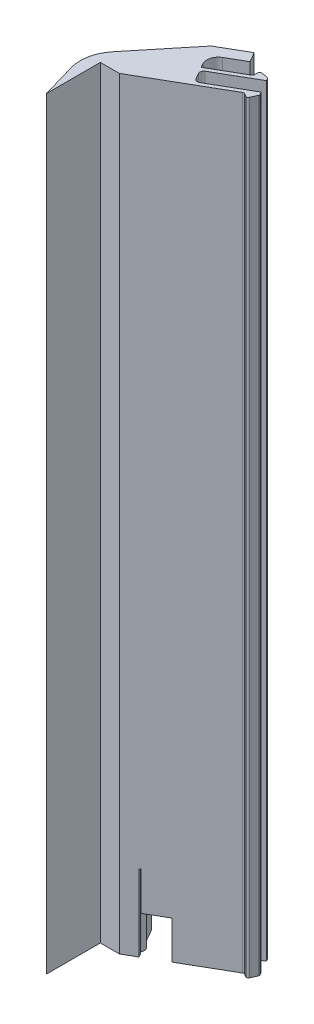
SolidWorks part; units mm, degrees
ref_plane "Front Plane" through (0, 0, 0) normal (0, 0, 1) x (1, 0, 0)
ref_plane "Top Plane" through (0, 0, 0) normal (0, 1, 0) x (1, 0, 0)
ref_plane "Right Plane" through (0, 0, 0) normal (1, 0, 0) x (0, 0, -1)
sketch "Sketch1" plane through (0, 0, 0) normal (0, 1, 0) x (1, 0, 0)
  line L0 (13.9271, 14.1754) -> (16.352, 13.8433)
  line L1 (16.352, 13.8433) -> (16.852, 12.9773)
  line L2 (13.9271, 14.1754) -> (13.9271, 12.4433)
  line L3 (2.5947, 5.9005) -> (3.0596, 5.0142)
  line L4 (13.9271, 12.4433) -> (2.5947, 5.9005)
  line L5 (18.752, 9.6864) -> (19.252, 8.8204)
  line L6 (19.252, 8.8204) -> (18.1539, 6.4543)
  line L7 (18.1539, 6.4543) -> (16.6539, 7.3204)
  line L8 (16.6539, 7.3204) -> (5.1142, 0.6579)
  line L9 (16.852, 12.9773) -> (3.0596, 5.0142)
  line L10 (18.752, 9.6864) -> (4.7191, 1.5845)
  line L11 (4.7191, 1.5845) -> (5.1142, 0.6579)
  dimension "D1" = 1
  dimension "D2" = 1
  dimension "D3" = 2.5
  dimension "D4" = 1
  dimension "D5" = 1
  dimension "D6" = 60
  dimension "D7" = 60
  dimension "D8" = 3
  dimension "D9" = 2.5
  dimension "D10" = 3.8
extrude "Boss-Extrude1" add sketch "Sketch1" along normal blind 200
fillet "Fillet1" radius 0.5 3 edges at (19.252, 100, -8.8204) (18.1539, 100, -6.4543) (16.6539, 100, -7.3204)
fillet "Fillet2" radius 0.5 3 edges at (16.352, 100, -13.8433) (13.9271, 100, -14.1754) (13.9271, 100, -12.4433)
sketch "Sketch2" plane through (0, 0, 0) normal (0, 1, 0) x (1, 0, 0)
  line L0 (8.1826, 2.4295) -> (3.2326, 11.0031)
  line L1 (5.1142, 0.6579) -> (16.4039, 7.176) construction
  line L2 (1.7326, 13.6012) -> (-13.1637, -4.6475)
  line L3 (-13.1637, -4.6475) -> (-9.0751, -18.7873)
  line L4 (-9.0751, -5.3031) -> (-9.0751, -305.3031) construction
  line L5 (-9.0751, -18.7873) -> (-9.0751, -4.6475)
  line L6 (-9.0751, -4.6475) -> (-4.0751, -4.6475)
  line L7 (8.1826, 2.4295) -> (-4.0751, -4.6475)
  line L8 (9.6431, 16.4363) -> (12.0181, 12.3227) construction
  line L9 (14.3058, 20.8603) -> (10.1922, 18.4853) construction
  line L10 (-4.0751, -5.3031) -> (-9.0751, -5.3031) construction
  line L11 (-4.0751, 60.1969) -> (-4.0751, -370.8031) construction
  line L12 (3.2326, 11.0031) -> (10.3931, 15.1372)
  line L13 (10.3931, 15.1372) -> (8.8931, 17.7353)
  line L14 (8.8931, 17.7353) -> (1.7326, 13.6012)
  dimension "D1" = 3
extrude "Boss-Extrude3" add sketch "Sketch2" along normal up to surface (200 mm away) up to face at (12.3433, 200, -11.5854)
fillet "Fillet3" radius 10 1 edges at (-13.1637, 100, 4.6475)
fillet "Fillet4" radius 1 2 edges at (5.7826, 100, -6.5864) (7.6826, 100, -3.2955)
fillet "Fillet5" radius 3 1 edges at (3.2326, 100, -11.0031)
sketch "Sketch3" plane through (0, 0, 0) normal (0, 1, 0) x (1, 0, 0)
  line L0 (-6.5899, 8.0163) -> (-2.3136, 0.6095)
  line L1 (-1.5636, -0.6895) -> (0.9704, -5.0785)
  line L2 (5.2826, 7.4524) -> (4.7326, 8.4051) construction
  line L7 (7.1826, 4.1615) -> (6.2826, 5.7204) construction
  line L8 (6.7326, 4.941) -> (-4.7829, -1.7076) construction
  line L9 (-4.0751, -4.6475) -> (16.4039, 7.176) construction
  line L10 (-6.9363, 7.8163) -> (-3.1217, 1.2092)
  line L11 (-1.4483, -1.6892) -> (0.6239, -5.2785)
  line L12 (-6.9363, 7.8163) -> (-6.5899, 8.0163)
  line L13 (0.6239, -5.2785) -> (0.9704, -5.0785)
  arc A0 (-2.3136, 0.6095) -> (-1.5636, -0.6895) centre (-3.0627, -0.689) ccw
  arc A2 (-3.1217, 1.2092) -> (-1.4483, -1.6892) centre (-3.0627, -0.689) ccw
  dimension "D1" = 1.5
  dimension "D2" = 10
  dimension "D3" = 0.4
extrude "Cut-Extrude2" cut sketch "Sketch3" along normal blind 20
sketch "Sketch4" plane through (0, 0, 0) normal (0, 1, 0) x (1, 0, 0)
  line L0 (-2.3136, 0.6095) -> (-5.0307, 5.3158)
  line L2 (-5.0307, 5.3158) -> (-2.0554, 8.9607)
  line L3 (1.7326, 13.6012) -> (-5.0307, 5.3158) construction
  line L4 (-2.0554, 8.9607) -> (4.6933, 0.4149)
  line L5 (-0.4776, -2.5705) -> (16.4039, 7.176) construction
  line L6 (4.6933, 0.4149) -> (-0.4776, -2.5705)
  line L7 (-0.4776, -2.5705) -> (-1.5636, -0.6895)
  arc A1 (-1.5636, -0.6895) -> (-2.3136, 0.6095) centre (-3.0627, -0.689) ccw
extrude "Cut-Extrude4" cut sketch "Sketch4" along normal blind 10
